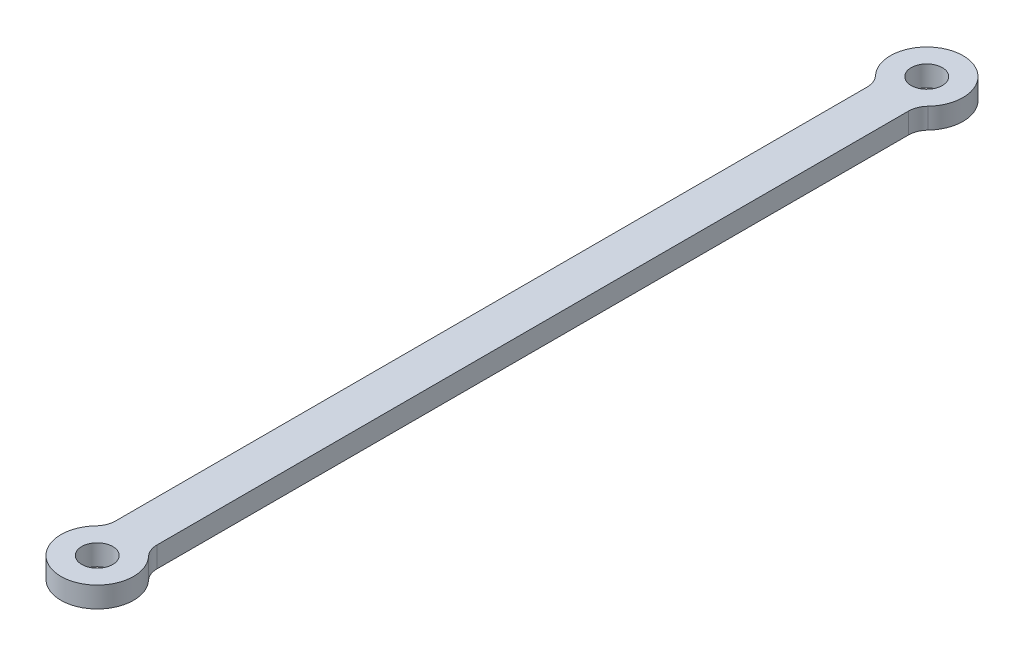
SolidWorks part; units mm, degrees
ref_plane "Front Plane" through (0, 0, 0) normal (0, 0, 1) x (1, 0, 0)
ref_plane "Top Plane" through (0, 0, 0) normal (0, 1, 0) x (1, 0, 0)
ref_plane "Right Plane" through (0, 0, 0) normal (1, 0, 0) x (0, 0, -1)
sketch "Sketch1" plane through (0, 0, 0) normal (0, 1, 0) x (1, 0, 0)
  line L0 (0, 0) -> (0, 101.6) construction
  line L1 (2.54, 3.6478) -> (2.54, 97.9522)
  line L2 (-2.54, 3.6478) -> (-2.54, 97.9522)
  line L3 (-2.54, 3.6478) -> (0, 3.6478) construction
  line L4 (0, 3.6478) -> (2.54, 3.6478) construction
  circle A0 centre (0, 101.6) radius 1.905
  arc A1 (2.54, 97.9522) -> (-2.54, 97.9522) centre (0, 101.6) ccw
  arc A2 (-2.54, 3.6478) -> (2.54, 3.6478) centre (0, 0) ccw
  circle A3 centre (0, 0) radius 1.905
  dimension "D1" = 3.81
  dimension "D2" = 2.54
  dimension "D3" = 101.6
  dimension "D4" = 5.08
extrude "Boss-Extrude1" add sketch "Sketch1" along normal blind 2.54
fillet "Fillet1" radius 2.54 4 edges at (2.54, 1.27, -3.6478) (-2.54, 1.27, -3.6478) (-2.54, 1.27, -97.9522) (2.54, 1.27, -97.9522)
